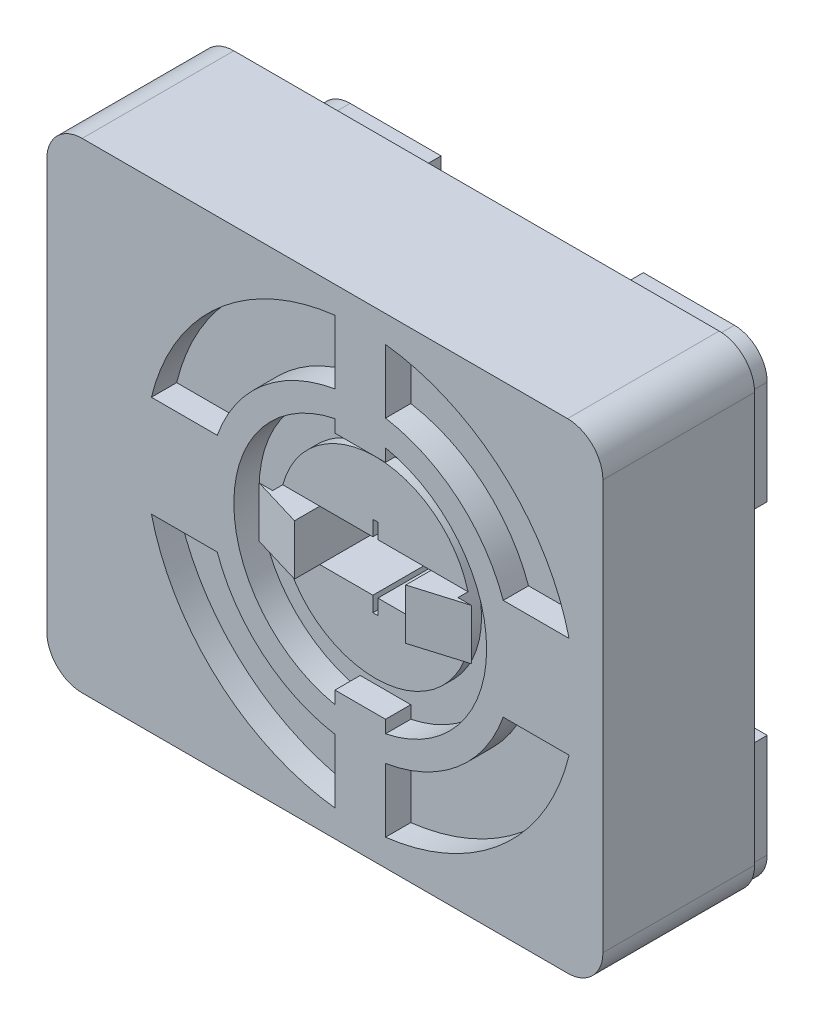
SolidWorks part; units mm, degrees
ref_plane "前视基准面" through (0, 0, 0) normal (0, 0, 1) x (1, 0, 0)
ref_plane "上视基准面" through (0, 0, 0) normal (0, 1, 0) x (1, 0, 0)
ref_plane "右视基准面" through (0, 0, 0) normal (1, 0, 0) x (0, 0, -1)
sketch "草图1" plane through (0, 0, 0) normal (0, 0, 1) x (1, 0, 0)
  line L0 (0, 0) -> (0, 9.5)
  line L1 (0, 9.5) -> (11, 9.5)
  line L2 (11, 9.5) -> (11, 0)
  line L3 (11, 0) -> (0, 0)
extrude "凸台-拉伸1" add sketch "草图1" along normal blind 3
sketch "草图2" plane through (0, 0, 3) normal (0, 0, 1) x (1, 0, 0)
  line L0 (9.0284, 5.75) -> (10.3307, 5.75)
  line L1 (3.3716, 3.75) -> (2.0693, 3.75)
  line L2 (2.0693, 5.75) -> (3.3716, 5.75)
  line L3 (5.7, 1.792) -> (5.7, 0.5295)
  line L4 (10.3307, 3.75) -> (9.0284, 3.75)
  line L5 (6.7, 1.792) -> (6.7, 0.5295)
  line L6 (5.7, 7.1995) -> (5.7, 6.95)
  line L7 (6.7, 7.1995) -> (6.7, 6.95)
  line L8 (5.7, 8.9705) -> (5.7, 7.708)
  line L9 (6.7, 8.9705) -> (6.7, 7.708)
  line L10 (6.7, 2.55) -> (6.7, 2.3005)
  line L11 (5.7, 2.55) -> (5.7, 2.3005)
  line L12 (5.7, 6.95) -> (6.7, 6.95)
  line L13 (5.7, 2.55) -> (6.7, 2.55)
  arc A0 (2.0693, 3.75) -> (5.7, 0.5295) centre (6.2, 4.75) ccw
  arc A1 (5.7, 7.1995) -> (5.7, 2.3005) centre (6.2, 4.75) ccw
  arc A2 (3.3716, 3.75) -> (5.7, 1.792) centre (6.2, 4.75) ccw
  arc A3 (9.0284, 5.75) -> (6.7, 7.708) centre (6.2, 4.75) ccw
  arc A4 (10.3307, 5.75) -> (6.7, 8.9705) centre (6.2, 4.75) ccw
  arc A5 (5.7, 7.708) -> (3.3716, 5.75) centre (6.2, 4.75) ccw
  arc A6 (5.7, 8.9705) -> (2.0693, 5.75) centre (6.2, 4.75) ccw
  arc A7 (6.7, 1.792) -> (9.0284, 3.75) centre (6.2, 4.75) ccw
  arc A8 (6.7, 0.5295) -> (10.3307, 3.75) centre (6.2, 4.75) ccw
  arc A9 (6.7, 2.3005) -> (6.7, 7.1995) centre (6.2, 4.75) ccw
extrude "切除-拉伸1" cut sketch "草图2" against normal blind 0.5
fillet "圆角1" radius 0.7 4 edges at (0, 0, 1.5) (0, 9.5, 1.5) (11, 9.5, 1.5) (11, 0, 1.5)
sketch "草图3" plane through (0, 0, 2.5) normal (0, 0, 1) x (1, 0, 0)
  circle A0 centre (6.2, 4.75) radius 1.9
extrude "凸台-拉伸2" add sketch "草图3" along normal blind 0.2
sketch "草图4" plane through (0, 0, 2.7) normal (0, 0, 1) x (1, 0, 0)
  line L0 (6.15, 5.55) -> (6.25, 5.55)
  line L1 (5.1, 4.75) -> (5.1, 5.25)
  line L2 (5.1, 5.25) -> (6.15, 5.25)
  line L3 (7.3, 5.25) -> (7.3, 4.25)
  line L4 (7.3, 4.25) -> (6.25, 4.25)
  line L5 (5.1, 4.25) -> (5.1, 4.75)
  line L6 (6.25, 5.55) -> (6.25, 5.25)
  line L7 (6.15, 5.55) -> (6.15, 5.25)
  line L8 (6.15, 4.25) -> (5.1, 4.25)
  line L9 (6.25, 4.25) -> (6.25, 3.95)
  line L10 (6.25, 3.95) -> (6.15, 3.95)
  line L11 (6.15, 3.95) -> (6.15, 4.25)
  line L12 (6.25, 5.25) -> (7.3, 5.25)
extrude "切除-拉伸2" cut sketch "草图4" against normal through all
sketch "草图5" plane through (0, 0, 2.7) normal (0, 0, 1) x (1, 0, 0)
  line L2 (5.1, 4.25) -> (5.1, 5.25)
  line L3 (5.1, 5.25) -> (4.367, 5.25)
  line L5 (5.1, 4.25) -> (4.367, 4.25)
  line L6 (7.3, 5.25) -> (8.033, 5.25)
  line L7 (7.3, 4.25) -> (7.3, 5.25)
  line L8 (7.3, 4.25) -> (8.033, 4.25)
  circle A2 centre (6.2, 4.75) radius 1.9 construction
  arc A3 (4.367, 5.25) -> (4.367, 4.25) centre (6.2, 4.75) ccw
  arc A4 (8.033, 4.25) -> (8.033, 5.25) centre (6.2, 4.75) ccw
extrude "凸台-拉伸3" add sketch "草图5" along normal blind 0.2
sketch "草图6" plane through (0, 4.25, 0) normal (0, -1, 0) x (1, 0, 0)
  line L0 (5.1, 2.9) -> (5.1, 3.2)
  line L1 (5.1, 2.9) -> (4.1, 2.9)
  line L2 (4.1, 2.9) -> (5.1, 3.2)
  line L3 (7.3, 2.9) -> (7.3, 3.2)
  line L4 (7.3, 2.9) -> (8.3, 2.9)
  line L5 (8.3, 2.9) -> (7.3, 3.2)
extrude "凸台-拉伸4" add sketch "草图6" along direction (0, 1, 0) on the side against the normal blind 1
sketch "草图7" plane through (0, 0, 0) normal (0, 0, -1) x (-1, 0, 0)
  circle A0 centre (-10, 8.5) radius 0.75
  circle A1 centre (-3, 8.5) radius 0.75
  circle A2 centre (-3, 1) radius 0.75
  circle A3 centre (-10, 1) radius 0.75
extrude "凸台-拉伸5" add sketch "草图7" along normal blind 0.5
sketch "草图8" plane through (0, 0, 0) normal (0, 0, -1) x (-1, 0, 0)
  line L3 (-2.05, 0.7) -> (-2.05, 2.75)
  line L4 (-10.95, 6.75) -> (-10.95, 8.8)
  line L5 (-10.45, 4.75) -> (-10.45, 6.75)
  line L6 (-2.7, 0.05) -> (-4.5, 0.05)
  line L7 (-10.95, 0.7) -> (-10.95, 2.75)
  line L8 (-10.3, 9.45) -> (-8.5, 9.45)
  line L9 (-10.45, 6.75) -> (-10.95, 6.75)
  line L10 (-10.45, 4.75) -> (-10.45, 2.75)
  line L11 (-10.45, 2.75) -> (-10.95, 2.75)
  line L13 (-6.5, 8.95) -> (-4.5, 8.95)
  line L14 (-4.5, 8.95) -> (-4.5, 9.45)
  line L15 (-6.5, 8.95) -> (-8.5, 8.95)
  line L16 (-8.5, 8.95) -> (-8.5, 9.45)
  line L17 (-4.5, 9.45) -> (-2.7, 9.45)
  line L18 (-2.05, 6.75) -> (-2.05, 8.8)
  line L19 (-2.55, 4.75) -> (-2.55, 6.75)
  line L20 (-2.55, 6.75) -> (-2.05, 6.75)
  line L21 (-2.55, 4.75) -> (-2.55, 2.75)
  line L22 (-2.55, 2.75) -> (-2.05, 2.75)
  line L23 (-8.5, 0.05) -> (-10.3, 0.05)
  line L24 (-6.5, 0.55) -> (-7.5, 0.55)
  line L25 (-7.5, 0.55) -> (-8.5, 0.55)
  line L26 (-8.5, 0.55) -> (-8.5, 0.05)
  line L27 (-6.5, 0.55) -> (-4.5, 0.55)
  line L28 (-4.5, 0.55) -> (-4.5, 0.05)
  arc A2 (-2.7, 9.45) -> (-2.05, 8.8) centre (-2.7, 8.8) cw
  arc A3 (-2.05, 0.7) -> (-2.7, 0.05) centre (-2.7, 0.7) cw
  arc A4 (-10.95, 0.7) -> (-10.3, 0.05) centre (-10.3, 0.7) ccw
  arc A5 (-10.3, 9.45) -> (-10.95, 8.8) centre (-10.3, 8.8) ccw
  circle A6 centre (-10, 8.5) radius 0.75
  circle A7 centre (-3, 8.5) radius 0.75
  circle A8 centre (-10, 1) radius 0.75
  circle A9 centre (-3, 1) radius 0.75
  circle A10 centre (-6.2, 4.75) radius 2
  point P18 (-6.5, 9.45)
extrude "凸台-拉伸6" add sketch "草图8" along normal blind 0.3
